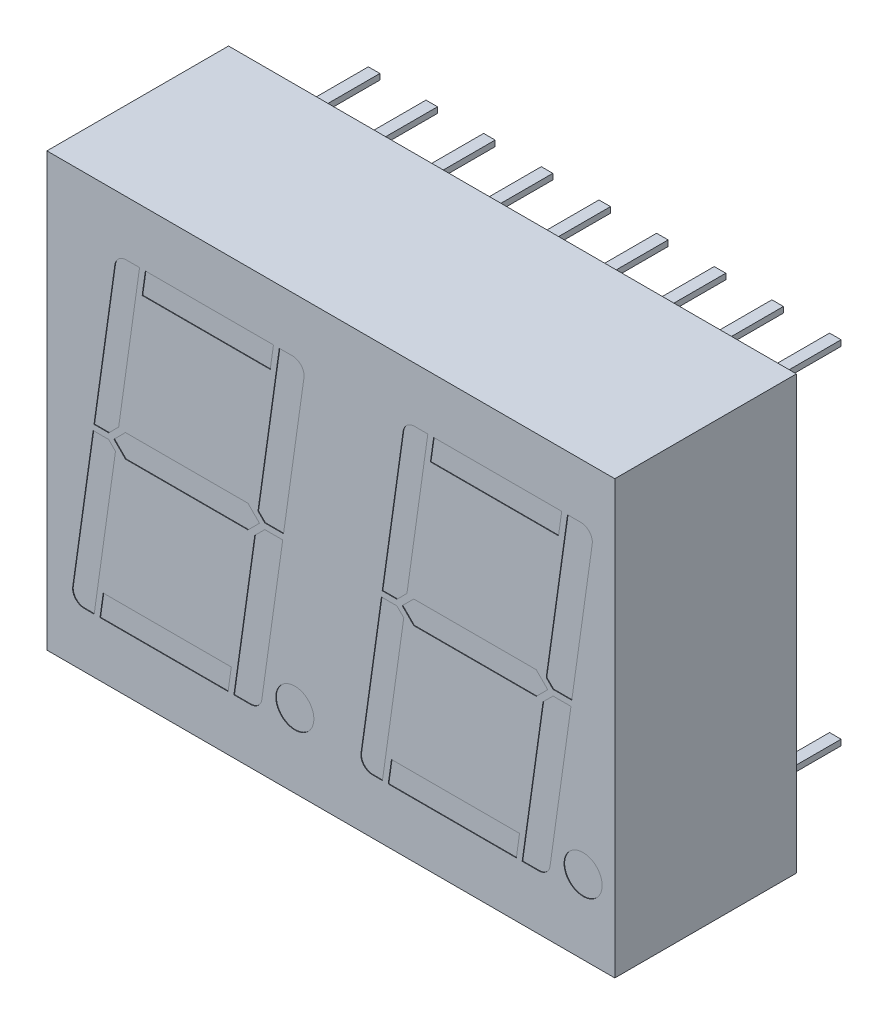
SolidWorks part; units mm, degrees
ref_plane "Front Plane" through (0, 0, 0) normal (0, 0, 1) x (1, 0, 0)
ref_plane "Top Plane" through (0, 0, 0) normal (0, 1, 0) x (1, 0, 0)
ref_plane "Right Plane" through (0, 0, 0) normal (1, 0, 0) x (0, 0, -1)
sketch "Sketch1" plane through (0, 0, 0) normal (0, 0, 1) x (1, 0, 0)
  line L0 (-12.5095, -9.525) -> (12.5095, 9.525) construction
  line L1 (-12.5095, 9.525) -> (12.5095, 9.525)
  line L2 (-12.5095, 9.525) -> (-12.5095, -9.525)
  line L3 (-12.5095, -9.525) -> (12.5095, -9.525)
  line L4 (12.5095, 9.525) -> (12.5095, -9.525)
  point P4 (0, 0)
  dimension "D1" = 19.05
  dimension "D2" = 25.019
extrude "Boss-Extrude1" add sketch "Sketch1" along normal blind 8.001
sketch "Sketch2" plane through (0, 0, 0) normal (0, 0, -1) x (-1, 0, 0)
  line L0 (0, 9.525) -> (0, -9.525) construction
  line L1 (-12.5095, 9.525) -> (12.5095, 9.525) construction
  line L2 (12.5095, -9.525) -> (-12.5095, -9.525) construction
  line L3 (-0.254, 7.62) -> (0.254, 7.62) construction
  line L4 (-12.5095, -9.525) -> (-12.5095, 9.525) construction
  line L5 (-12.5095, 0) -> (12.5095, 0) construction
  line L6 (12.5095, 9.525) -> (12.5095, -9.525) construction
  line L7 (-0.254, 7.747) -> (0.254, 7.747)
  line L8 (-0.254, 7.747) -> (-0.254, 7.493)
  line L9 (-0.254, 7.493) -> (0.254, 7.493)
  line L10 (0.254, 7.747) -> (0.254, 7.493)
  point P18 (0, 7.62)
  dimension "D1" = 0.508
  dimension "D2" = 0.254
  dimension "D3" = 7.62
extrude "Boss-Extrude2" add sketch "Sketch2" along normal blind 4.064
pattern_linear "LPattern1" count 5 spacing 2.54 along (-1, 0, 0) count 2 spacing 15.24 along (0, -1, 0) of "Boss-Extrude2"
pattern_linear "LPattern2" count 5 spacing 2.54 along (1, 0, 0) count 2 spacing 15.24 along (0, -1, 0) of "Boss-Extrude2"
sketch "Sketch4" plane through (0, 0, 8.001) normal (0, 0, 1) x (1, 0, 0)
  line L0 (0, 9.525) -> (0, -9.525) construction
  line L1 (12.5095, 9.525) -> (-12.5095, 9.525) construction
  line L2 (-12.5095, -9.525) -> (12.5095, -9.525) construction
  line L3 (-12.5095, 0) -> (12.5095, 0) construction
  line L4 (-12.5095, 9.525) -> (-12.5095, -9.525) construction
  line L5 (12.5095, -9.525) -> (12.5095, 9.525) construction
  line L6 (-5.3505, 7.112) -> (-7.3495, -7.112) construction
  line L7 (-9.5562, 0) -> (-9.0482, 0.508)
  line L8 (-9.0482, 0.508) -> (-3.6518, 0.508)
  line L9 (-9.7884, 0.127) -> (-9.3482, 0.5672)
  line L10 (-9.3482, 0.5672) -> (-8.4284, 7.112)
  line L11 (-8.4284, 7.112) -> (-9.0128, 7.112)
  line L12 (-9.5159, 6.6747) -> (-10.4361, 0.127)
  line L13 (-10.4361, 0.127) -> (-9.7884, 0.127)
  line L14 (-5.3505, 7.112) -> (-8.1719, 7.112)
  line L15 (-8.1719, 7.112) -> (-8.3133, 6.1059)
  line L16 (-8.3133, 6.1059) -> (-5.4919, 6.1059)
  line L17 (-6.35, -9.525) -> (-6.35, 9.525) construction
  line L18 (-9.0482, -0.508) -> (-3.6518, -0.508)
  line L19 (-9.5562, 0) -> (-9.0482, -0.508)
  line L20 (-3.1438, 0) -> (-3.6518, 0.508)
  line L21 (-9.3022, 0.254) -> (-9.4818, 0.4336) construction
  line L22 (-8.2426, 6.6089) -> (-8.4942, 6.6443) construction
  line L23 (-9.1153, 9.525) -> (-10.4539, 0) construction
  line L24 (-3.1438, 0) -> (-3.6518, -0.508)
  line L25 (-2.0854, 0.127) -> (-2.9116, 0.127)
  line L26 (-2.9116, 0.127) -> (-3.212, 0.4274)
  line L27 (-3.212, 0.4274) -> (-2.2725, 7.112)
  line L28 (-2.2725, 7.112) -> (-1.6881, 7.112)
  line L29 (-1.1851, 6.5333) -> (-2.0854, 0.127)
  line L30 (-3.5444, -7.112) -> (-4.2716, -7.112)
  line L31 (-9.3022, -0.254) -> (-9.4818, -0.4336) construction
  line L32 (-4.2716, -7.112) -> (-3.3518, -0.5672)
  line L33 (-10.4718, -0.127) -> (-9.7884, -0.127)
  line L34 (-2.1211, -0.127) -> (-3.0413, -6.6747)
  line L35 (-10.4275, -7.112) -> (-10.8691, -7.112)
  line L36 (-3.3978, 0.254) -> (-3.2182, 0.4336) construction
  line L37 (-11.3721, -6.5333) -> (-10.4718, -0.127)
  line L38 (-9.7884, -0.127) -> (-9.488, -0.4274)
  line L39 (-9.488, -0.4274) -> (-10.4275, -7.112)
  line L40 (-5.4919, 6.1059) -> (-2.6704, 6.1059)
  line L41 (-2.6704, 6.1059) -> (-2.529, 7.112)
  line L42 (-2.529, 7.112) -> (-5.3505, 7.112)
  line L43 (-2.1211, -0.127) -> (-2.9116, -0.127)
  line L44 (-2.9116, -0.127) -> (-3.3518, -0.5672)
  line L45 (-2.5997, 6.6089) -> (-2.3482, 6.5736) construction
  line L46 (-3.3978, -0.254) -> (-3.2182, -0.4336) construction
  line L47 (-9.976, 3.4008) -> (-8.9699, 3.2595) construction
  line L48 (-7.2081, -6.1059) -> (-10.0296, -6.1059)
  line L49 (-10.0296, -6.1059) -> (-10.171, -7.112)
  line L50 (-10.171, -7.112) -> (-7.3495, -7.112)
  line L51 (-7.3495, -7.112) -> (-4.5281, -7.112)
  line L52 (-4.5281, -7.112) -> (-4.3867, -6.1059)
  line L53 (-4.3867, -6.1059) -> (-7.2081, -6.1059)
  arc A0 (-9.5159, 6.6747) -> (-9.0128, 7.112) centre (-9.0128, 6.604) cw
  arc A1 (-11.3721, -6.5333) -> (-10.8691, -7.112) centre (-10.8691, -6.604) ccw
  arc A2 (-3.0413, -6.6747) -> (-3.5444, -7.112) centre (-3.5444, -6.604) cw
  arc A3 (-1.1851, 6.5333) -> (-1.6881, 7.112) centre (-1.6881, 6.604) ccw
  circle A4 centre (-1.5875, -6.2738) radius 0.8382
  point P12 (-6.35, 0)
  point P32 (-6.35, 0.508)
  point P34 (-6.35, -0.508)
  dimension "D9" = 0.508
  dimension "D14" = 0.508
  dimension "D15" = 1.6764
  dimension "D16" = 4.7625
  dimension "D1" = 6.35
  dimension "D2" = 0.508
  dimension "D3" = 45
  dimension "D4" = 4.064
  dimension "D5" = 0.254
  dimension "D6" = 0.127
  dimension "D7" = 3.175
  dimension "D8" = 7.112
  dimension "D10" = 1.016
  dimension "D11" = 14.224
  dimension "D12" = 8
  dimension "D13" = 0.127
extrude "Cut-Extrude1" cut sketch "Sketch4" against normal blind 0.0254
pattern_linear "LPattern3" count 2 spacing 12.7 along (1, 0, 0) of "Cut-Extrude1"
